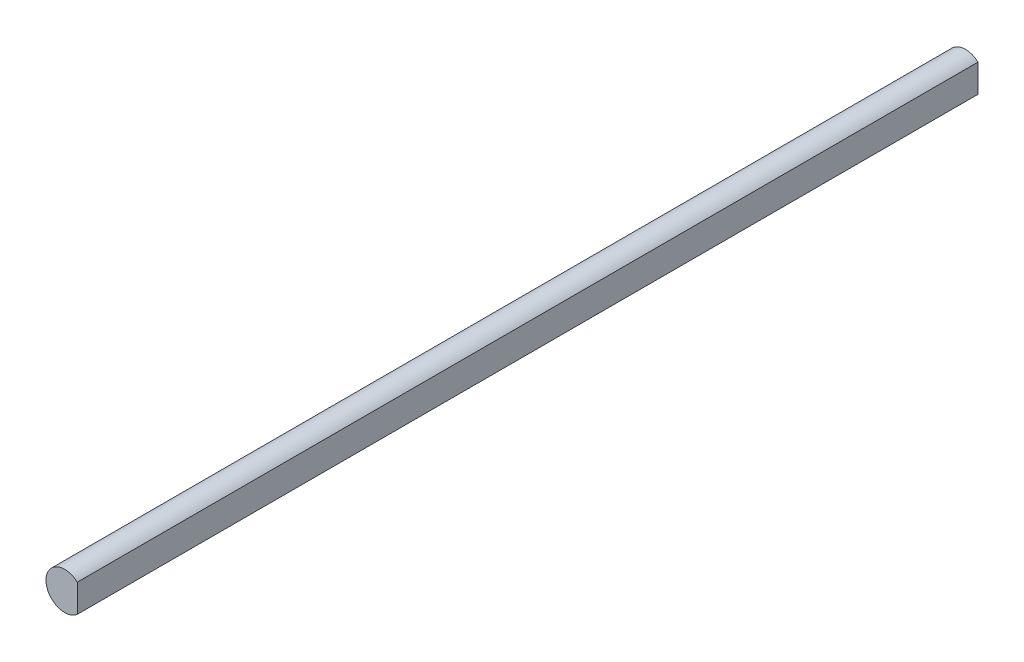
SolidWorks part; units mm, degrees
ref_plane "Alzado" through (0, 0, 0) normal (0, 0, 1) x (1, 0, 0)
ref_plane "Planta" through (0, 0, 0) normal (0, 1, 0) x (1, 0, 0)
ref_plane "Vista lateral" through (0, 0, 0) normal (1, 0, 0) x (0, 0, -1)
sketch "Croquis1" plane through (0, 0, 0) normal (0, 0, 1) x (1, 0, 0)
  circle A0 centre (0, 0) radius 2.5
  dimension "D1" = 5
extrude "Saliente-Extruir1" add sketch "Croquis1" along normal blind 120
sketch "Croquis2" plane through (0, 0, 0) normal (0, 0, -1) x (-1, 0, 0)
  line L0 (-1.6729, 1.8578) -> (-1.6729, -1.8578)
  arc A0 (-1.6729, 1.8578) -> (-1.6729, -1.8578) centre (0, 0) ccw
extrude "Cortar-Extruir1" cut sketch "Croquis2" against normal through all
